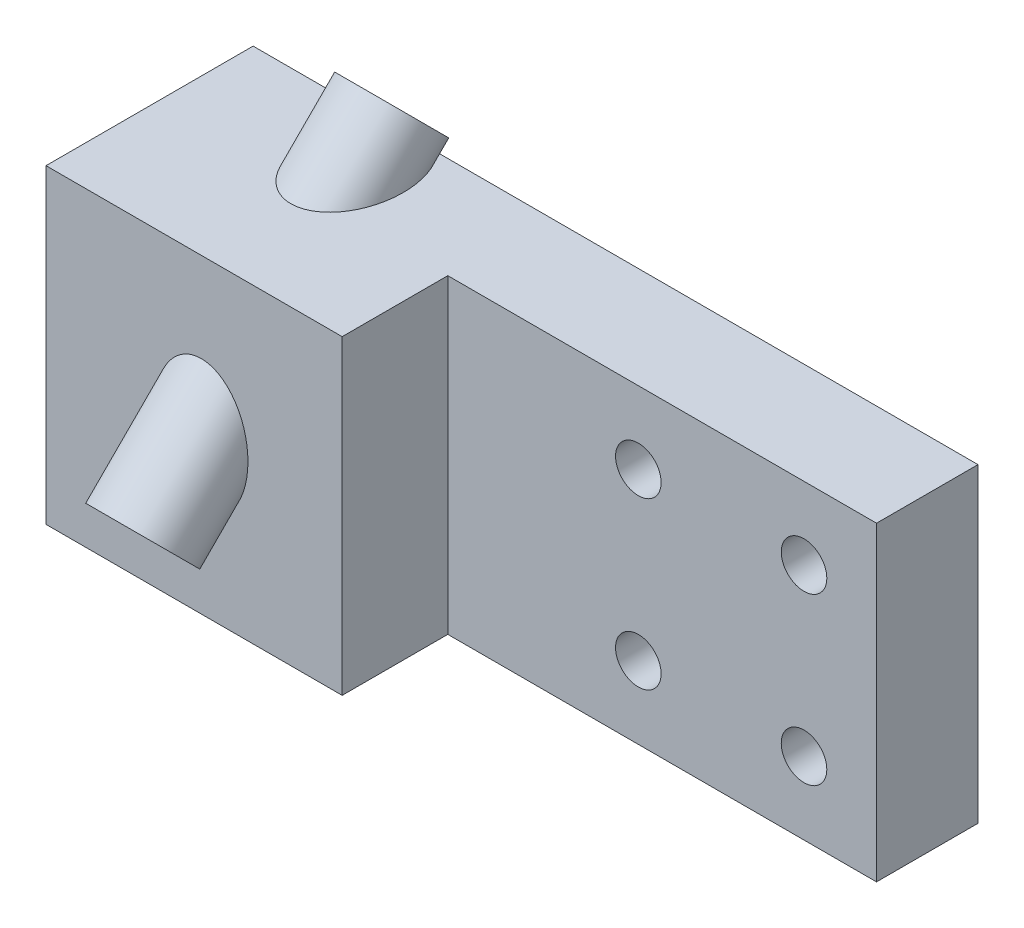
SolidWorks part; units mm, degrees
ref_plane "前视基准面" through (0, 0, 0) normal (0, 0, 1) x (1, 0, 0)
ref_plane "上视基准面" through (0, 0, 0) normal (0, 1, 0) x (1, 0, 0)
ref_plane "右视基准面" through (0, 0, 0) normal (1, 0, 0) x (0, 0, -1)
sketch "Sketch1" plane through (0, 0, 0) normal (0, 0, 1) x (1, 0, 0)
  line L0 (0, -7.5) -> (7.5, -7.5) construction
  line L1 (0, 0) -> (15, 0)
  line L2 (0, 0) -> (0, -15)
  line L3 (0, -15) -> (15, -15)
  line L4 (15, 0) -> (15, -15)
  line L6 (3.5, -11.5) -> (11.5, -11.5) construction
  line L7 (3.5, -11.5) -> (3.5, -3.5) construction
  line L8 (3.5, -3.5) -> (11.5, -3.5) construction
  line L9 (11.5, -11.5) -> (11.5, -3.5) construction
  line L10 (3.5, -11.5) -> (11.5, -3.5) construction
  line L11 (3.5, -3.5) -> (11.5, -11.5) construction
  circle A0 centre (3.5, -3.5) radius 1.1
  circle A1 centre (11.5, -3.5) radius 1.1
  circle A2 centre (11.5, -11.5) radius 1.1
  circle A3 centre (3.5, -11.5) radius 1.1
  dimension "D6" = 2.2
  dimension "D7" = 2.2
  dimension "D8" = 2.2
  dimension "D9" = 2.2
  dimension "D1" = 15
  dimension "D2" = 15
  dimension "D3" = 7.5
  dimension "D4" = 8
  dimension "D5" = 8
extrude "Extrude1" add sketch "Sketch1" along normal blind 4
sketch "Sketch2" plane through (0, 0, 4) normal (0, 0, 1) x (1, 0, 0)
  line L0 (0, -7.5) -> (15, -7.5) construction
  line L1 (0, 0) -> (0, -15) construction
  line L2 (15, -15) -> (15, 0) construction
ref_plane "Plane1" through (0, -5.75, 5.75) normal (0, -0.7071, 0.7071) x (1, 0, 0)
sketch "Sketch3" plane through (0, -5.75, 5.75) normal (0, -0.7071, 0.7071) x (1, 0, 0)
  line L0 (0, -2.4749) -> (15, -2.4749) construction
  circle A0 centre (7.5, -2.4749) radius 2
  dimension "D1" = 4
extrude "Extrude2" add sketch "Sketch3" along normal blind 60 and the other way blind 4
sketch "Sketch4" plane through (0, -48.1764, 48.1764) normal (0, -0.7071, 0.7071) x (1, 0, 0)
  line L0 (0, -2.4749) -> (15, -2.4749) construction
  circle A0 centre (7.5, -2.4749) radius 1.75
  dimension "D1" = 3.5
extrude "Extrude3" add sketch "Sketch4" along normal blind 3
sketch "Sketch5" plane through (0, -50.2977, 50.2977) normal (0, -0.7071, 0.7071) x (-1, 0, 0)
  line L0 (0, 2.4749) -> (-15, 2.4749) construction
  circle A0 centre (-7.5, 2.4749) radius 2
  dimension "D1" = 4
extrude "Extrude4" add sketch "Sketch5" along normal blind 3
sketch "Sketch6" plane through (0, 0, 4) normal (0, 0, 1) x (1, 0, 0)
  line L1 (0, 0) -> (35, 0)
  line L2 (0, 0) -> (0, -15)
  line L3 (0, -15) -> (35, -15)
  line L4 (35, 0) -> (35, -15)
  dimension "D1" = 35
extrude "Extrude5" add sketch "Sketch6" against normal blind 10
sketch "Sketch7" plane through (0, 0, 4) normal (0, 0, 1) x (1, 0, 0)
  line L0 (35, 0) -> (35, -15) construction
  line L1 (35, -15) -> (20, -15) construction
  line L2 (0, -15) -> (35, -15) construction
  line L3 (20, -15) -> (20, 0) construction
  line L4 (35, 0) -> (0, 0) construction
  line L5 (20, 0) -> (35, 0) construction
  line L6 (35, 0) -> (20, -15) construction
  line L7 (20, 0) -> (35, -15) construction
  line L9 (23.5, -11.5) -> (31.5, -11.5) construction
  line L10 (23.5, -11.5) -> (23.5, -3.5) construction
  line L11 (23.5, -3.5) -> (31.5, -3.5) construction
  line L12 (31.5, -11.5) -> (31.5, -3.5) construction
  line L13 (23.5, -11.5) -> (31.5, -3.5) construction
  line L14 (23.5, -3.5) -> (31.5, -11.5) construction
  circle A0 centre (31.5, -3.5) radius 1.1
  circle A1 centre (31.5, -11.5) radius 1.1
  circle A2 centre (23.5, -11.5) radius 1.1
  circle A3 centre (23.5, -3.5) radius 1.1
  point P10 (27.5, -7.5)
  dimension "D2" = 2.2
  dimension "D1" = 8
  dimension "D3" = 4
extrude "Extrude6" cut sketch "Sketch7" against normal blind 29
sketch "Sketch8" plane through (0, -15, 0) normal (0, -1, 0) x (-1, 0, 0)
  line L0 (-35, 1) -> (-35, -1.1)
  line L1 (-35, 6) -> (-35, -4) construction
  line L2 (-35, -1.1) -> (-16.3, -1.1)
  line L3 (-16.3, -1.1) -> (-16.3, 1.1)
  line L4 (-16.3, 1.1) -> (-35, 1.1)
  line L5 (-35, 1.1) -> (-35, -1.1)
  line M3 (-35, 6) -> (-35, -4)
  dimension "D1" = 18.7
extrude "Extrude7" cut sketch "Sketch8" against normal blind 29 contours L3 L4 L2 M3
sketch "草图1" plane through (0, -5.75, 5.75) normal (0, -0.7071, 0.7071) x (1, 0, 0)
  line L0 (0, -2.4749) -> (15, -2.4749) construction
  circle A0 centre (7.5, -2.4749) radius 1.5
  dimension "D1" = 3
extrude "切除-拉伸1" cut sketch "草图1" against normal blind 13
sketch "草图2" plane through (0, 0, 0) normal (-1, 0, 0) x (0, 0, 1)
  line L1 (4, 0) -> (64.8144, 0)
  line L2 (4, 0) -> (4, -56.6537)
  line L3 (4, -56.6537) -> (64.8144, -56.6537)
  line L4 (64.8144, 0) -> (64.8144, -56.6537)
extrude "切除-拉伸2" cut sketch "草图2" against normal blind 13
sketch "草图4" plane through (0, -5.75, 5.75) normal (0, -0.7071, 0.7071) x (1, 0, 0)
  line L0 (0, -2.4749) -> (15, -2.4749) construction
  circle A0 centre (7.5, -2.4749) radius 1.5
  circle A1 centre (7.5, -2.4749) radius 2.25
  dimension "D1" = 4.5
extrude "凸台-拉伸1" add sketch "草图4" along normal blind 4 and the other way blind 13
sketch "草图5" plane through (0, -15, 0) normal (0, -1, 0) x (-1, 0, 0)
  line L1 (-16.3, -1.1) -> (-35, -1.1)
  line L2 (-16.3, -1.1) -> (-16.3, -2.1)
  line L3 (-16.3, -2.1) -> (-35, -2.1)
  line L4 (-35, -1.1) -> (-35, -2.1)
  dimension "D1" = 1
extrude "切除-拉伸3" cut sketch "草图5" against normal blind 21
sketch "草图6" plane through (0, -15, 0) normal (0, -1, 0) x (-1, 0, 0)
  line L1 (-16.3, -2.1) -> (-35, -2.1)
  line L2 (-16.3, -2.1) -> (-16.3, -4)
  line L3 (-16.3, -4) -> (-35, -4)
  line L4 (-35, -2.1) -> (-35, -4)
extrude "切除-拉伸4" cut sketch "草图6" against normal blind 21
sketch "草图7" plane through (16.3, 0, 0) normal (1, 0, 0) x (0, 0, -1)
  line L0 (-4, 0) -> (-4, -15) construction
  line L1 (-4, 0) -> (1.1, 0)
  line L2 (-4, 0) -> (-4, -15)
  line L3 (-4, -15) -> (1.1, -15)
  line L4 (1.1, 0) -> (1.1, -15)
extrude "切除-拉伸5" cut sketch "草图7" against normal blind 2
